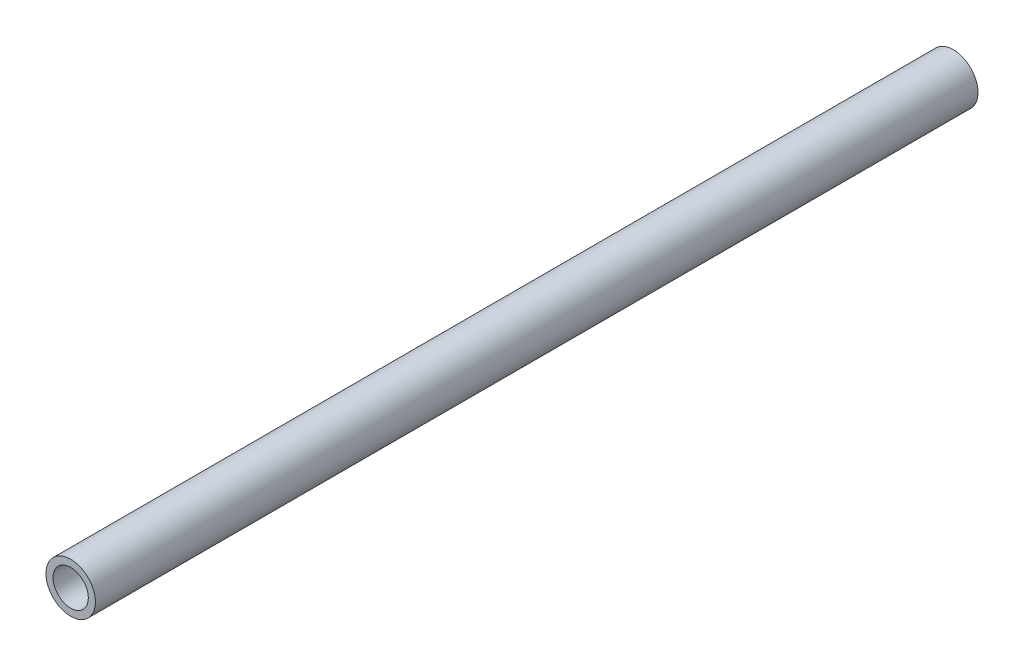
SolidWorks part; units mm, degrees
ref_plane "정면" through (0, 0, 0) normal (0, 0, 1) x (1, 0, 0)
ref_plane "윗면" through (0, 0, 0) normal (0, 1, 0) x (1, 0, 0)
ref_plane "우측면" through (0, 0, 0) normal (1, 0, 0) x (0, 0, -1)
sketch "스케치1" plane through (0, 0, 0) normal (0, 0, 1) x (1, 0, 0)
  circle A0 centre (0, 0) radius 7
  circle A1 centre (0, 0) radius 5
  dimension "D1" = 10
  dimension "D2" = 14
extrude "보스-돌출1" add sketch "스케치1" along normal blind 250
